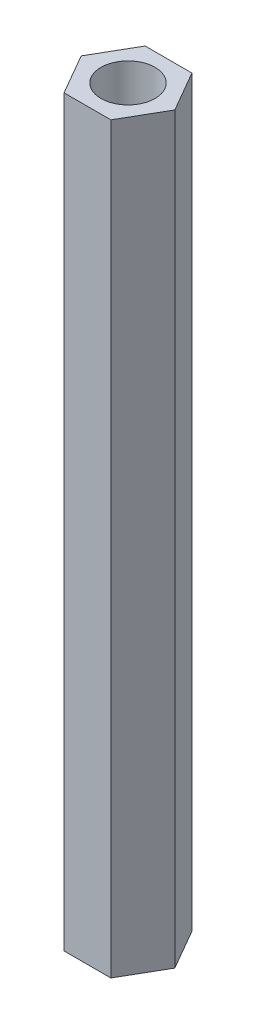
SolidWorks part; units mm, degrees
ref_plane "Front Plane" through (0, 0, 0) normal (0, 0, 1) x (1, 0, 0)
ref_plane "Top Plane" through (0, 0, 0) normal (0, 1, 0) x (1, 0, 0)
ref_plane "Right Plane" through (0, 0, 0) normal (1, 0, 0) x (0, 0, -1)
sketch "草图1" plane through (0, 0, 0) normal (0, 1, 0) x (1, 0, 0)
  line L1 (1.7321, 3) -> (-1.7321, 3)
  line L2 (-1.7321, 3) -> (-3.4641, 0)
  line L3 (-3.4641, 0) -> (-1.7321, -3)
  line L4 (-1.7321, -3) -> (1.7321, -3)
  line L5 (1.7321, -3) -> (3.4641, 0)
  line L6 (3.4641, 0) -> (1.7321, 3)
  circle A0 centre (0, 0) radius 3 construction
  circle A1 centre (0, 0) radius 2
  dimension "D2" = 4
  dimension "D1" = 6
extrude "凸台-拉伸1" add sketch "草图1" along normal blind 55
